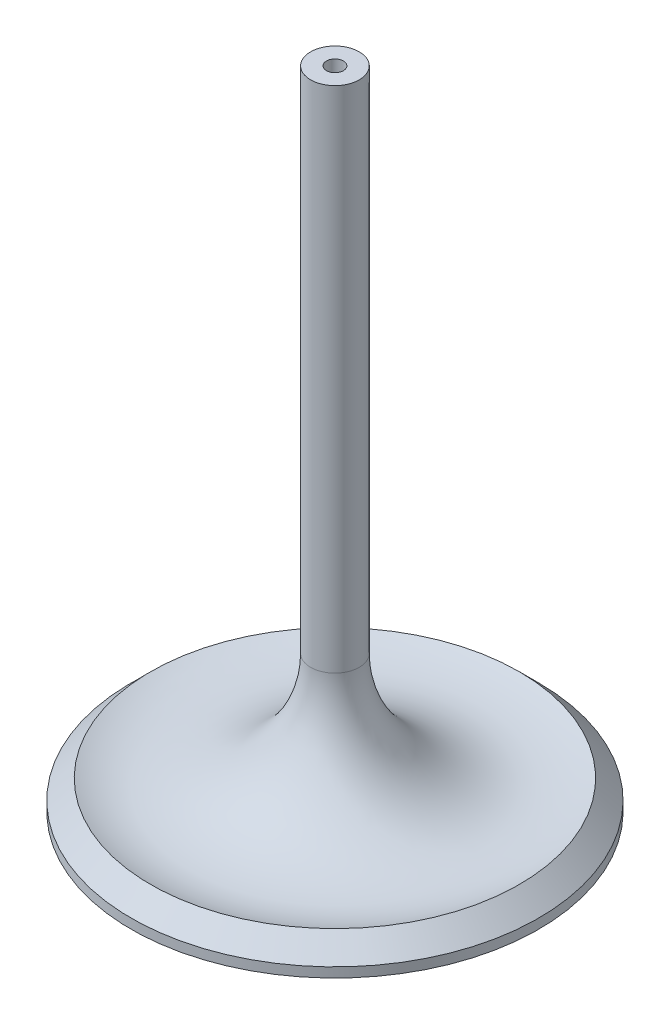
SolidWorks part; units mm, degrees
ref_plane "Front Plane" through (0, 0, 0) normal (0, 0, 1) x (1, 0, 0)
ref_plane "Top Plane" through (0, 0, 0) normal (0, 1, 0) x (1, 0, 0)
ref_plane "Right Plane" through (0, 0, 0) normal (1, 0, 0) x (0, 0, -1)
sketch "Sketch1" plane through (0, 0, 0) normal (0, 0, 1) x (1, 0, 0)
  line L0 (0, 0) -> (0, 84.55)
  line L1 (0, 84.55) -> (3.18, 84.55)
  line L2 (3.18, 84.55) -> (3.18, 17.9547)
  line L3 (24.13, 3.81) -> (26.67, 1.27)
  line L4 (26.67, 1.27) -> (26.67, 0)
  line L5 (26.67, 0) -> (0, 0)
  arc A0 (3.18, 17.9547) -> (24.13, 3.81) centre (18.43, 17.9547) ccw
  dimension "D7" = 15.25
  dimension "D1" = 84.55
  dimension "D2" = 26.67
  dimension "D3" = 3.18
  dimension "D4" = 1.27
  dimension "D5" = 3.81
  dimension "D6" = 45
revolve "Revolve1" add sketch "Sketch1" angle 360 about L0
sketch "Sketch2" plane through (0, 0, 0) normal (0, -1, 0) x (1, 0, 0)
  circle A0 centre (0, 0) radius 14.5109
extrude "Cut-Extrude1" cut sketch "Sketch2" against normal blind 1.2
sketch "Sketch3" plane through (0, 84.55, 0) normal (0, 1, 0) x (1, 0, 0)
  circle A0 centre (0, 0) radius 1.1065
extrude "Cut-Extrude2" cut sketch "Sketch3" against normal blind 95.2
sketch "Sketch4" plane through (0, 1.2, 0) normal (0, -1, 0) x (1, 0, 0)
  circle A0 centre (0, 0) radius 9.0625
extrude "Cut-Extrude3" cut sketch "Sketch4" against normal blind 1
